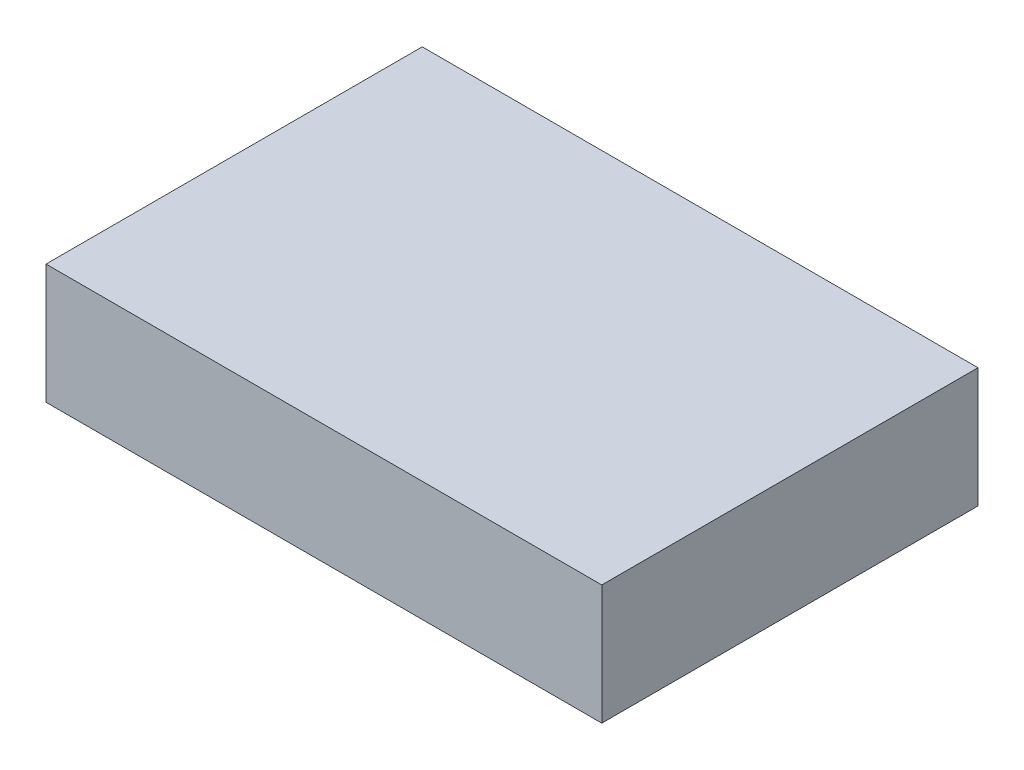
SolidWorks part; units mm, degrees
ref_plane "Front Plane" through (0, 0, 0) normal (0, 0, 1) x (1, 0, 0)
ref_plane "Top Plane" through (0, 0, 0) normal (0, 1, 0) x (1, 0, 0)
ref_plane "Right Plane" through (0, 0, 0) normal (1, 0, 0) x (0, 0, -1)
sketch "Sketch1" plane through (0, 0, 0) normal (0, 1, 0) x (1, 0, 0)
  line L1 (0, 0) -> (16.51, 0)
  line L2 (0, 0) -> (0, 11.176)
  line L3 (0, 11.176) -> (16.51, 11.176)
  line L4 (16.51, 0) -> (16.51, 11.176)
  dimension "D1" = 11.176
  dimension "D2" = 16.51
extrude "Extrude1" add sketch "Sketch1" along normal blind 3.556
